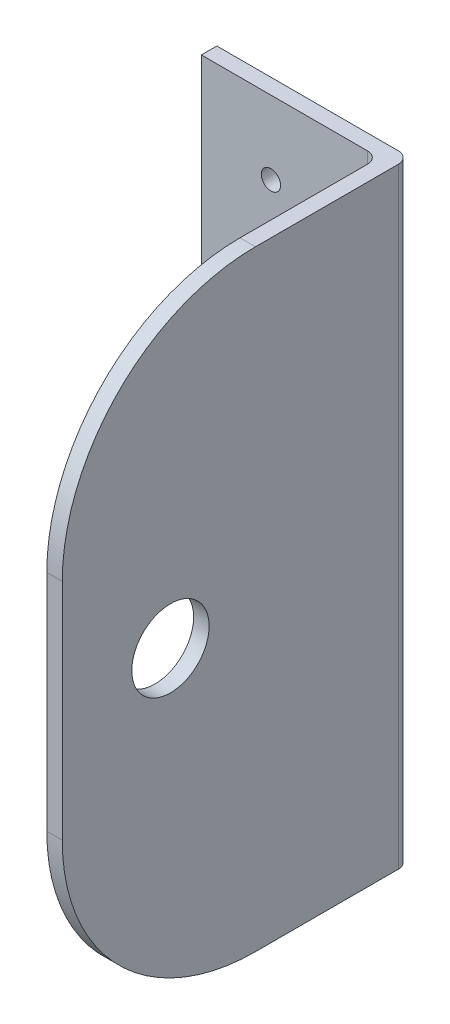
SolidWorks part; units mm, degrees
ref_plane "Front Plane" through (0, 0, 0) normal (0, 0, 1) x (1, 0, 0)
ref_plane "Top Plane" through (0, 0, 0) normal (0, 1, 0) x (1, 0, 0)
ref_plane "Right Plane" through (0, 0, 0) normal (1, 0, 0) x (0, 0, -1)
sketch "Sketch1" plane through (0, 0, 0) normal (0, 1, 0) x (1, 0, 0)
  line L0 (0, 0) -> (0, -2)
  line L1 (0, -2) -> (23, -2)
  line L2 (0, 0) -> (25, 0)
  line L3 (25, 0) -> (25, -45)
  line L4 (25, -45) -> (23, -45)
  line L5 (23, -45) -> (23, -2)
  dimension "D1" = 25
  dimension "D2" = 2
  dimension "D3" = 45
  dimension "D4" = 2
extrude "Boss-Extrude1" add sketch "Sketch1" along normal blind 79
sketch "Sketch2" plane through (25, 0, 0) normal (1, 0, 0) x (0, 0, -1)
  line L0 (-45, 39.5) -> (-36, 39.5) construction
  line L1 (-45, 79) -> (-45, 0) construction
  circle A0 centre (-31, 39.5) radius 5
  dimension "D1" = 10
  dimension "D2" = 9
extrude "Cut-Extrude1" cut sketch "Sketch2" against normal through all
sketch "Sketch3" plane through (25, 0, 0) normal (1, 0, 0) x (0, 0, -1)
  line L0 (0, 79) -> (-20, 79) construction
  line L1 (-45, 79) -> (0, 79) construction
  line L2 (0, 0) -> (-20, 0) construction
  line L3 (-45, 0) -> (0, 0) construction
  line L4 (-45, 39.5) -> (-45, 54) construction
  line L5 (-45, 79) -> (-45, 0) construction
  line L6 (-45, 39.5) -> (-45, 25) construction
  line L7 (-45, 54) -> (-56.0297, 54)
  line L8 (-56.0297, 54) -> (-56.0297, 83.569)
  line L9 (-56.0297, 83.569) -> (-20, 83.569)
  line L10 (-20, 83.569) -> (-20, 79)
  line L11 (-20, 79) -> (-20.1702, 78.9365)
  line L12 (-20, 0) -> (-20, -10.4027)
  line L13 (-20, -10.4027) -> (-50.6404, -10.4027)
  line L14 (-50.6404, -10.4027) -> (-50.6404, 25)
  line L15 (-50.6404, 25) -> (-45, 25)
  arc A0 (-45, 54) -> (-20, 79) centre (-20, 54) cw
  arc A1 (-45, 25) -> (-20, 0) centre (-20, 25) ccw
  line M2 (-45, 0) -> (0, 0)
  line M4 (0, 79) -> (-45, 79)
  line M5 (-45, 79) -> (-45, 0)
  dimension "D1" = 20
extrude "Cut-Extrude3" cut sketch "Sketch3" against normal through all contours L10 L9 L8 L7 M5 M4 | L15 L14 L13 L12 M2 M5 | A1 M5 M2 | A0 M5 M4
fillet "Fillet1" radius 1.5 2 edges at (23, 39.5, 2) (25, 39.5, 0)
sketch "Sketch5" plane through (0, 0, 0) normal (0, 0, -1) x (-1, 0, 0)
  line L0 (-18, 69.5) -> (-9, 69.5) construction
  line L1 (-9, 69.5) -> (-9, 9.5) construction
  line L2 (-9, 9.5) -> (-18, 9.5) construction
  line L3 (-18, 9.5) -> (-18, 69.5) construction
  line L4 (-18, 69.5) -> (-18, 79) construction
  line L5 (-23.5, 79) -> (0, 79) construction
  line L6 (-18, 9.5) -> (-18, 0) construction
  line L7 (-23.5, 0) -> (0, 0) construction
  line L8 (-18, 69.5) -> (-25, 69.5) construction
  line L9 (-25, 0) -> (-25, 79) construction
  circle A0 centre (-18, 69.5) radius 1.25
  circle A1 centre (-9, 69.5) radius 1.25
  circle A2 centre (-9, 9.5) radius 1.25
  circle A3 centre (-18, 9.5) radius 1.25
  dimension "D4" = 2.5
  dimension "D1" = 60
  dimension "D2" = 7
  dimension "D3" = 9
extrude "Cut-Extrude4" cut sketch "Sketch5" against normal through all
